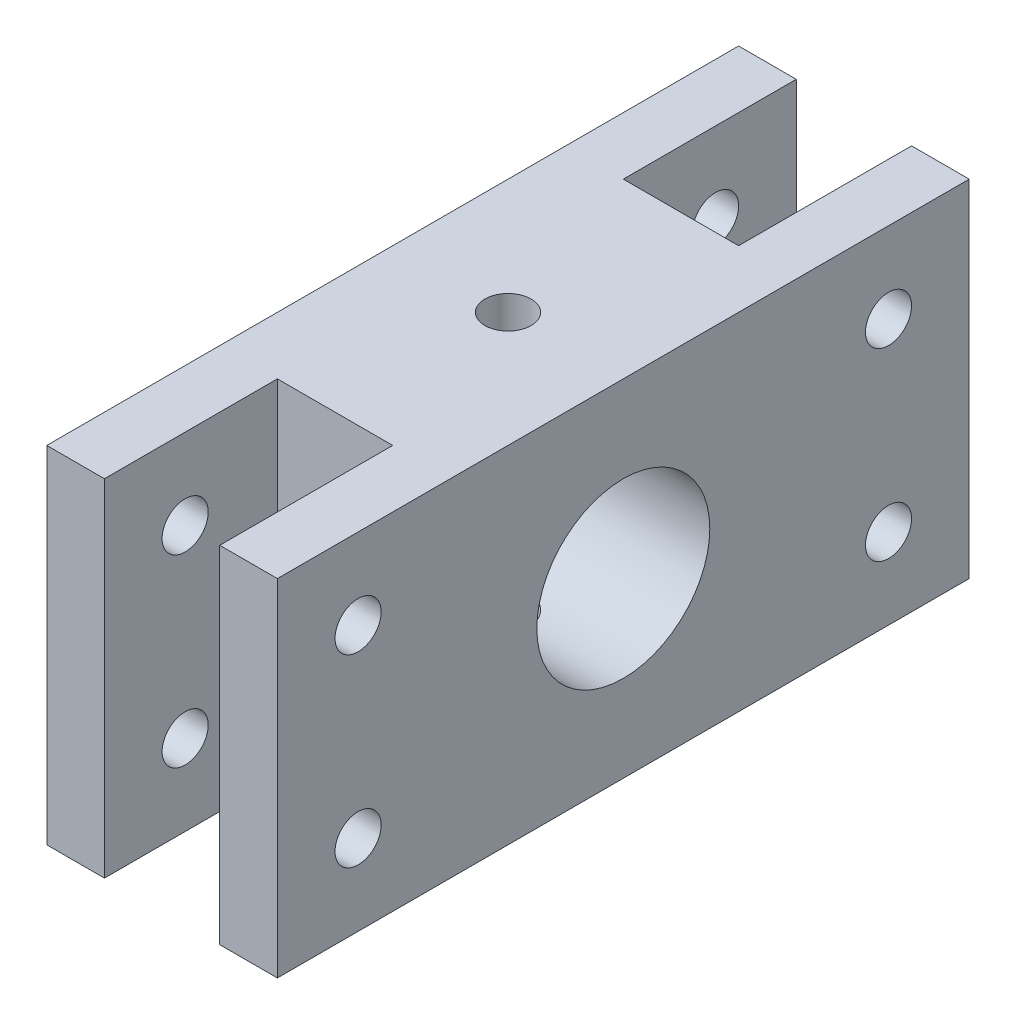
SolidWorks part; units mm, degrees
ref_plane "정면" through (0, 0, 0) normal (0, 0, 1) x (1, 0, 0)
ref_plane "윗면" through (0, 0, 0) normal (0, 1, 0) x (1, 0, 0)
ref_plane "우측면" through (0, 0, 0) normal (1, 0, 0) x (0, 0, -1)
sketch "스케치1" plane through (0, 0, 0) normal (1, 0, 0) x (0, 0, -1)
  line L0 (0, 24.1656) -> (0, -23.006) construction
  line L1 (-30, 15) -> (30, 15)
  line L2 (-30, 15) -> (-30, -15)
  line L3 (-30, -15) -> (30, -15)
  line L4 (30, 15) -> (30, -15)
  line L5 (-30, 15) -> (30, -15) construction
  line L6 (-30, -15) -> (30, 15) construction
  line L7 (-42.7163, 0) -> (48.1791, 0) construction
  circle A0 centre (-23, 8) radius 2
  circle A1 centre (-23, -8) radius 2
  circle A2 centre (23, -8) radius 2
  circle A3 centre (23, 8) radius 2
  point P0 (0, 0)
  dimension "D3" = 4
  dimension "D5" = 7
  dimension "D1" = 60
  dimension "D2" = 30
  dimension "D4" = 7
extrude "보스-돌출1" add sketch "스케치1" along normal blind 20
sketch "스케치2" plane through (0, 15, 0) normal (0, 1, 0) x (1, 0, 0)
  line L0 (-9.7231, 0) -> (28.9218, 0) construction
  line L1 (5, 30) -> (5, 15)
  line L2 (20, 30) -> (0, 30) construction
  line L3 (5, 15) -> (15, 15)
  line L4 (15, 30) -> (15, 15)
  line L5 (10, 32.2306) -> (10, -33.7445) construction
  line L6 (0, 30) -> (0, -30) construction
  line L7 (20, 30) -> (20, -30) construction
  line L8 (5, 30) -> (15, 30)
  line L9 (5, -30) -> (5, -15)
  line L10 (5, -15) -> (15, -15)
  line L11 (15, -30) -> (15, -15)
  line L12 (5, -30) -> (15, -30)
  point P11 (10, 15)
  dimension "D1" = 5
  dimension "D2" = 5
  dimension "D3" = 15
extrude "컷-돌출1" cut sketch "스케치2" against normal through all
sketch "스케치3" plane through (0, 0, 0) normal (-1, 0, 0) x (0, 0, 1)
  circle A0 centre (0, 0) radius 7.5
  dimension "D1" = 15
extrude "컷-돌출2" cut sketch "스케치3" against normal blind 20
sketch "스케치4" plane through (0, 15, 0) normal (0, 1, 0) x (1, 0, 0)
  circle A0 centre (10, 0) radius 2
extrude "컷-돌출3" cut sketch "스케치4" against normal through all
